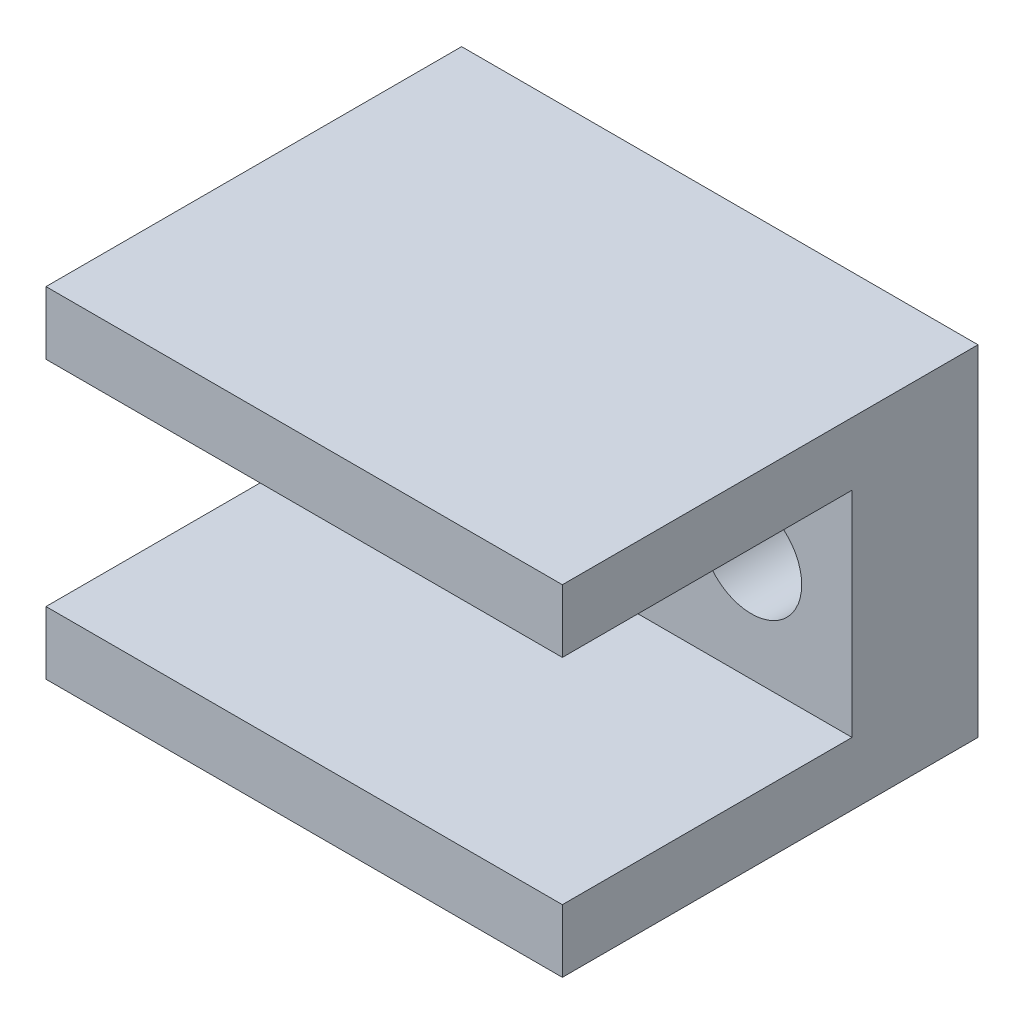
SolidWorks part; units mm, degrees
ref_plane "Front Plane" through (0, 0, 0) normal (0, 0, 1) x (1, 0, 0)
ref_plane "Top Plane" through (0, 0, 0) normal (0, 1, 0) x (1, 0, 0)
ref_plane "Right Plane" through (0, 0, 0) normal (1, 0, 0) x (0, 0, -1)
sketch "Sketch1" plane through (0, 0, 0) normal (0, 0, 1) x (1, 0, 0)
  line L1 (-20.5, -13.5) -> (20.5, -13.5)
  line L2 (-20.5, -13.5) -> (-20.5, 13.5)
  line L3 (-20.5, 13.5) -> (20.5, 13.5)
  line L4 (20.5, -13.5) -> (20.5, 13.5)
  line L5 (-20.5, -13.5) -> (20.5, 13.5) construction
  line L6 (-20.5, 13.5) -> (20.5, -13.5) construction
  point P0 (0, 0)
  dimension "D1" = 27
  dimension "D2" = 41
extrude "Boss-Extrude1" add sketch "Sketch1" along normal blind 10 contours L3 L4 L1 L2
sketch "Sketch2" plane through (0, 0, 10) normal (0, 0, 1) x (1, 0, 0)
  line L0 (55, 0) -> (-55, 0) construction
  line L1 (-20.5, 8.5) -> (20.5, 8.5)
  line L2 (-20.5, 8.5) -> (-20.5, 13.5)
  line L3 (-20.5, 13.5) -> (20.5, 13.5)
  line L4 (20.5, 8.5) -> (20.5, 13.5)
  line L5 (-20.5, 8.5) -> (20.5, 13.5) construction
  line L6 (-20.5, 13.5) -> (20.5, 8.5) construction
  line L11 (-20.5, 13.5) -> (20.5, 13.5) construction
  line L12 (20.5, -13.5) -> (20.5, 13.5) construction
  line L13 (-20.5, -8.5) -> (20.5, -13.5) construction
  line L14 (-20.5, -13.5) -> (20.5, -8.5) construction
  line L15 (-20.5, -13.5) -> (20.5, -13.5)
  line L16 (20.5, -8.5) -> (20.5, -13.5)
  line L17 (-20.5, -8.5) -> (20.5, -8.5)
  line L18 (-20.5, -8.5) -> (-20.5, -13.5)
  point P0 (0, 11)
  point P5 (-0.8398, 21.1171)
  point P6 (0, 0)
  point P15 (0, -11)
  dimension "D1" = 5
extrude "Boss-Extrude2" add sketch "Sketch2" along normal blind 23
sketch "Sketch3" plane through (0, 0, 10) normal (0, 0, 1) x (1, 0, 0)
  line L0 (-12.5, 0) -> (12.5, 0) construction
  circle A0 centre (-12.5, 0) radius 4
  circle A1 centre (12.5, 0) radius 4
  point P4 (0, 0)
  point P6 (0, 0)
  dimension "D1" = 8
  dimension "D2" = 25
extrude "Cut-Extrude1" cut sketch "Sketch3" against normal up to next
